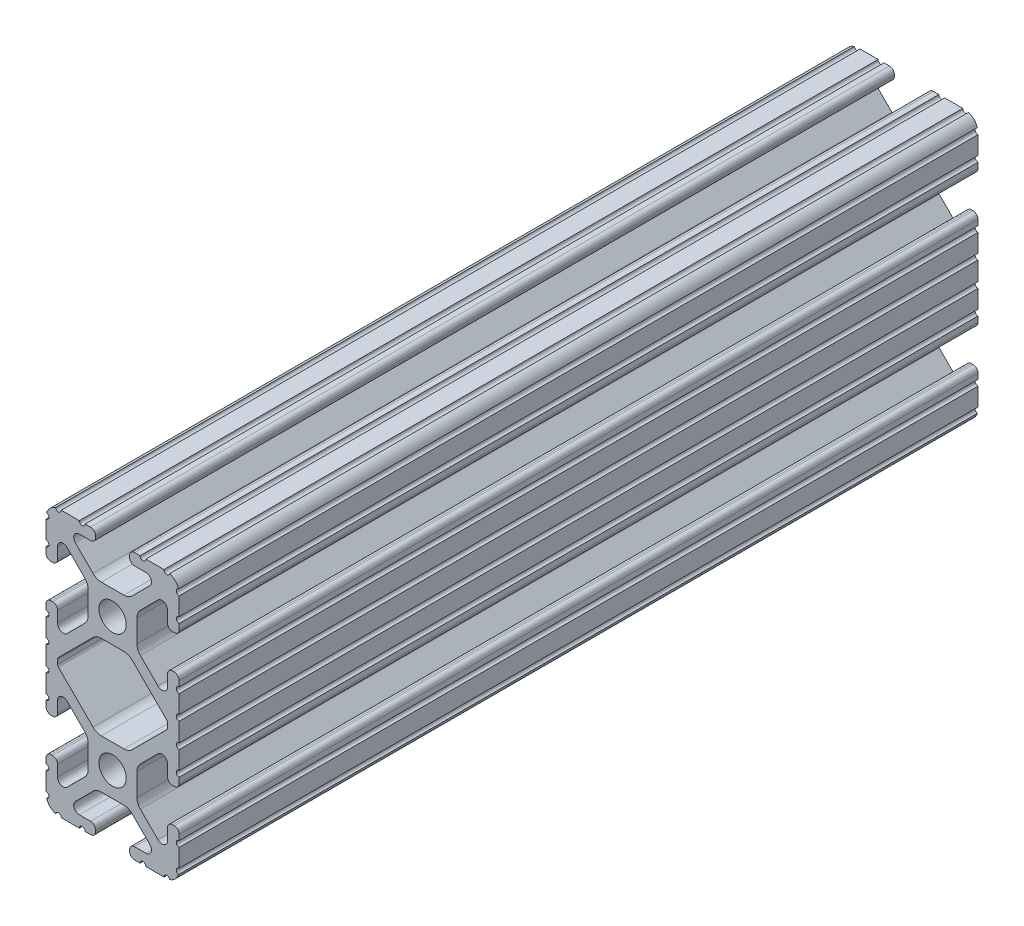
SolidWorks part; units mm, degrees
ref_plane "Front Plane" through (0, 0, 0) normal (0, 0, 1) x (1, 0, 0)
ref_plane "Top Plane" through (0, 0, 0) normal (0, 1, 0) x (1, 0, 0)
ref_plane "Right Plane" through (0, 0, 0) normal (1, 0, 0) x (0, 0, -1)
sketch "Sketch2" plane through (0, 0, 0) normal (0, 0, 1) x (1, 0, 0)
  line L0 (0, 25.4) -> (0, -25.4) construction
  line L1 (-12.7, 0) -> (12.7, 0) construction
  line L2 (3.2512, -25.4) -> (12.7, -25.4)
  line L3 (12.7, -25.4) -> (12.7, -15.9512)
  line L4 (3.2512, -25.4) -> (3.2512, -23.1902)
  line L5 (3.2512, -23.1902) -> (8.9276, -23.1902)
  line L6 (8.9276, -23.1902) -> (3.0856, -17.3482)
  line L7 (0, -12.7) -> (12.7, -25.4) construction
  line L8 (12.7, -15.9512) -> (10.4902, -15.9512)
  line L9 (10.4902, -15.9512) -> (10.4902, -21.6276)
  line L10 (10.4902, -21.6276) -> (4.6482, -15.7856)
  circle A0 centre (0, -12.7) radius 2.6035
  arc A1 (6.3485, -23.1902) -> (7.1039, -21.3665) centre (6.3485, -22.1219) ccw construction
  point P8 (0, -17.3482)
  dimension "Center Hole Diameter" = 5.207
  dimension "Rail Height" = 50.8
  dimension "Rail Width" = 25.4
  dimension "T-Slot Width" = 6.5024
  dimension "Slot Inner Width" = 14.8336
  dimension "Thickness" = 2.2098
  dimension "Slot Depth" = 5.842
  dimension "D1" = 2.2098
  dimension "C to C" = 25.4
sketch "Sketch3" plane through (0, 0, 0) normal (1, 0, 0) x (0, 0, -1)
  line L0 (-76.2, -25.4) -> (76.2, -25.4) construction
  line L1 (-50.8, 0) -> (50.8, 0) construction
  dimension "Length" = 152.4
  dimension "D1" = 25.4
sketch "Sketch4" plane through (0, 0, 0) normal (0, 0, 1) x (1, 0, 0)
  line L0 (4.1904, -25.4) -> (10.1173, -25.4)
  line L1 (3.2512, -25.4) -> (12.7, -25.4) construction
  line L2 (3.2512, -25.4) -> (3.2512, -23.1902) construction
  line L3 (3.2512, -23.1902) -> (8.9276, -23.1902) construction
  line L4 (3.2512, -24.1294) -> (3.2512, -24.4608)
  line L5 (4.1904, -23.1902) -> (6.3485, -23.1902)
  line L6 (0, -17.3482) -> (2.164, -17.3482)
  line L7 (8.9276, -23.1902) -> (3.0856, -17.3482) construction
  line L8 (3.7373, -17.9999) -> (7.1039, -21.3665)
  line L9 (12.7, -25.4) -> (12.7, -15.9512) construction
  line L10 (10.4902, -21.6276) -> (4.6482, -15.7856) construction
  line L11 (10.4902, -15.9512) -> (10.4902, -21.6276) construction
  line L12 (10.4902, -19.0485) -> (10.4902, -16.8904)
  line L13 (12.7, -15.9512) -> (10.4902, -15.9512) construction
  line L14 (11.4294, -15.9512) -> (11.7608, -15.9512)
  line L15 (12.7, -16.8904) -> (12.7, -22.8173)
  line L16 (8.6665, -19.8039) -> (5.2999, -16.4373)
  line L17 (4.6482, -12.7) -> (4.6482, -14.864)
  line L19 (0, -17.3482) -> (0, -15.3035)
  line L20 (0, 25.4) -> (0, -25.4) construction
  line L21 (4.6482, -12.7) -> (2.6035, -12.7)
  arc A0 (3.2512, -24.4608) -> (4.1904, -25.4) centre (4.1904, -24.4608) ccw
  circle A1 centre (0, -12.7) radius 2.6035 construction
  arc A2 (3.2512, -24.1294) -> (4.1904, -23.1902) centre (4.1904, -24.1294) cw
  arc A3 (6.3485, -23.1902) -> (7.1039, -21.3665) centre (6.3485, -22.1219) ccw
  arc A4 (2.164, -17.3482) -> (3.7373, -17.9999) centre (2.164, -19.5732) cw
  arc A5 (10.1173, -25.4) -> (12.7, -22.8173) centre (10.1173, -22.8173) ccw
  arc A6 (8.6665, -19.8039) -> (10.4902, -19.0485) centre (9.4219, -19.0485) ccw
  arc A7 (10.4902, -16.8904) -> (11.4294, -15.9512) centre (11.4294, -16.8904) cw
  arc A8 (11.7608, -15.9512) -> (12.7, -16.8904) centre (11.7608, -16.8904) cw
  arc A9 (5.2999, -16.4373) -> (4.6482, -14.864) centre (6.8732, -14.864) cw
  arc A11 (0, -15.3035) -> (2.6035, -12.7) centre (0, -12.7) ccw
  dimension "D1" = 2.5827
  dimension "D2" = 2.225
  dimension "D3" = 0.9392
extrude "Boss-Extrude1" add sketch "Sketch4" along normal mid plane 152.4
sketch "Sketch5" plane through (0, 0, 0) normal (0, 0, 1) x (1, 0, 0)
  line L0 (3.2512, -25.4) -> (12.7, -25.4) construction
  line L1 (4.1904, -23.1902) -> (6.3485, -23.1902) construction
  line L3 (0, -12.7) -> (12.7, -25.4) construction
  line L4 (6.3485, -23.1902) -> (6.3485, -25.4) construction
  line L5 (8.9276, -23.1902) -> (3.0856, -17.3482) construction
  circle A0 centre (10.3562, -25.4) radius 0.5524
  circle A1 centre (5.796, -25.4) radius 0.5524
  circle A2 centre (12.7, -23.0562) radius 0.5524
  circle A3 centre (12.7, -18.496) radius 0.5524
  point P10 (5.2694, -23.1902)
  point P12 (9.4219, -19.0485)
  dimension "D1" = 1.1049
extrude "Cut-Extrude1" cut sketch "Sketch5" against normal through all both and the other way through all
mirror "Mirror1" about plane through (4.6482, -12.7, 76.2) normal (0, -1, 0) of bodies 137 134
sketch "Sketch6" plane through (0, 0, 0) normal (0, 0, 1) x (1, 0, 0)
  line L0 (12.7, -1.7914) -> (12.7, 0)
  line L1 (12.7, 0) -> (9.8037, 0)
  line L2 (-12.7, 0) -> (12.7, 0) construction
  line L3 (9.8037, 0) -> (9.8037, -2.3438)
  line L4 (9.8037, -2.3438) -> (12.1476, -2.3438)
  circle A0 centre (12.7, -2.3438) radius 0.5524 construction
  arc A1 (12.7, -1.7914) -> (12.1476, -2.3438) centre (12.7, -2.3438) ccw
  arc A4 (12.58, -1.8046) -> (12.7, -2.8963) centre (12.7, -2.3438) ccw construction
  arc A6 (9.8037, 0) -> (10.8954, -0.12) centre (10.3562, 0) ccw construction
extrude "Boss-Extrude2" add sketch "Sketch6" along normal mid plane 152.4
sketch "Sketch7" plane through (0, 0, 0) normal (0, 0, 1) x (1, 0, 0)
  line L0 (5.4206, -5.7168) -> (10.3284, -0.809)
  line L1 (3.7373, -7.4001) -> (7.1039, -4.0335) construction
  line L2 (10.4902, -0.4184) -> (10.4902, 0)
  line L3 (0, 0) -> (10.4902, 0)
  line L4 (-12.7, 0) -> (12.7, 0) construction
  line L5 (0, 0) -> (5.4206, -5.7168)
  arc A0 (10.3284, -0.809) -> (10.4902, -0.4184) centre (9.9377, -0.4184) ccw
  arc A3 (12.7, -1.7914) -> (12.7, -2.8963) centre (12.7, -2.3438) ccw construction
extrude "Cut-Extrude2" cut sketch "Sketch7" against normal through all both and the other way through all
mirror "Mirror2" about plane through (0, 0, 0) normal (0, 1, 0) of bodies 139 135
mirror "Mirror3" about plane through (0, 0, 0) normal (1, 0, 0) of bodies 136
equation "\"D1@Boss-Extrude1\"=\"Length@Sketch3\""
equation "\"D1@Sketch2\"=\"Thickness@Sketch2\""
equation "\"D2@Sketch4\"=\"Slot Inner Width@Sketch2\"*0.15"
equation "\"D1@Sketch4\"=\"D3@Sketch4\"*2.75"
equation "\"D3@Sketch4\"=\"Thickness@Sketch2\"*0.425"
equation "\"D1@Sketch5\"=\"Thickness@Sketch2\"*0.5"
equation "\"D1@Boss-Extrude2\"=\"Length@Sketch3\""
